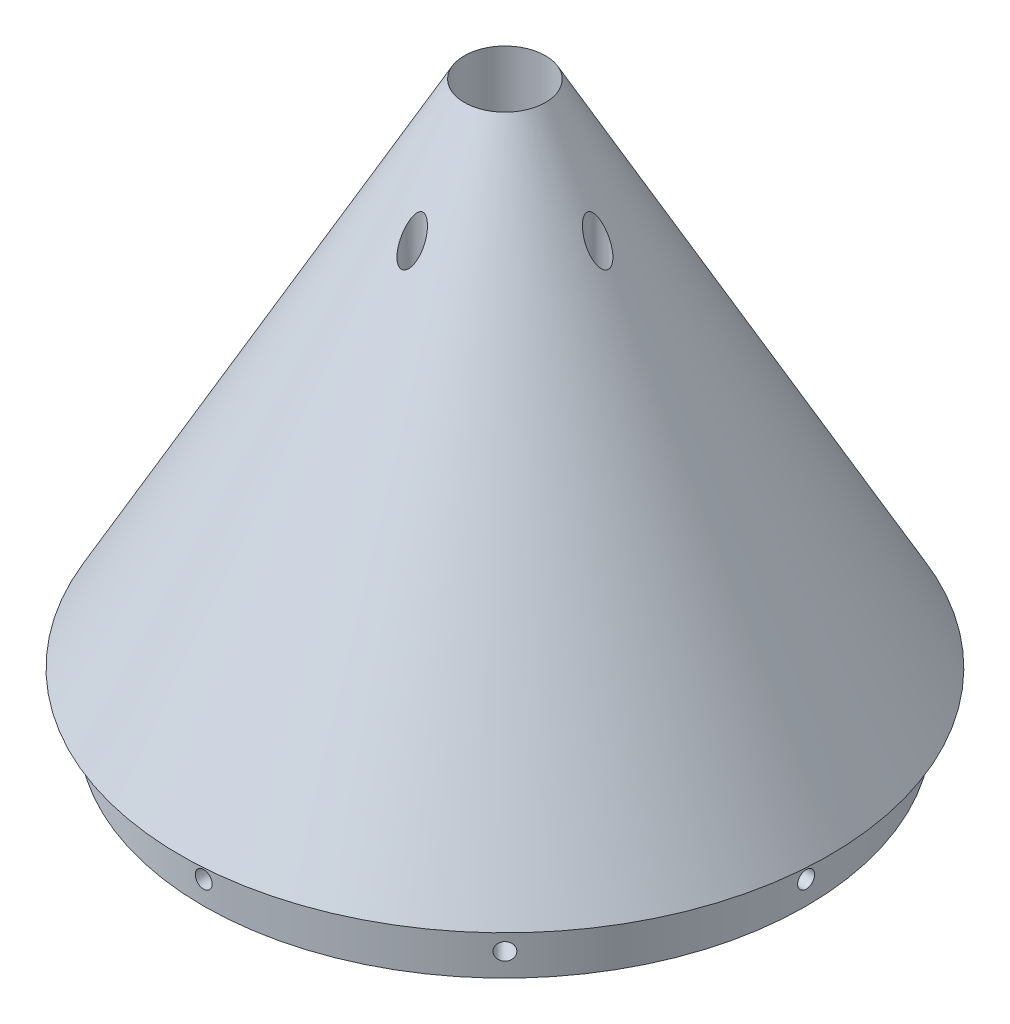
SolidWorks part; units mm, degrees
other "Markup1"
sketch "Sketch7" plane through (49.25, 60, 49.25) normal (0.0252, 0.7674, 0.6407) x (0.9994, -0.0343, 0.0017)
sketch "Sketch10" plane through (49.25, 120, 49.25) normal (0.0252, 0.7674, 0.6407) x (0.9994, -0.0343, 0.0017)
ref_plane "Front Plane" through (0, 0, 0) normal (0, 0, 1) x (1, 0, 0)
ref_plane "Top Plane" through (0, 0, 0) normal (0, 1, 0) x (1, 0, 0)
ref_plane "Right Plane" through (0, 0, 0) normal (1, 0, 0) x (0, 0, -1)
sketch "Sketch1" plane through (0, 0, 0) normal (0, 1, 0) x (1, 0, 0)
  circle A0 centre (0, 0) radius 65
  circle A1 centre (0, 0) radius 8.75
  dimension "D1" = 130
  dimension "D2" = 17.5
extrude "Boss-Extrude1" add sketch "Sketch1" along normal blind 12 contours A0
ref_plane "Plane1" through (-65, 0, 0) normal (-1, 0, 0) x (0, 0, 1)
sketch "Sketch2" plane through (-65, 0, 0) normal (-1, 0, 0) x (0, 0, 1)
  line L0 (0, 0) -> (0, 5)
  circle A0 centre (0, 5) radius 1.825
  dimension "D1" = 3.65
extrude "Cut-Extrude1" cut sketch "Sketch2" against normal blind 11
pattern_circular "CirPattern1" count 8 over 360 about axis through (0, 0, 0) along (0, 1, 0) of "Cut-Extrude1"
sketch "Sketch6" plane through (0, 0, 0) normal (0, 0, 1) x (1, 0, 0)
  line L3 (-8.75, 12) -> (-8.75, 122)
  line L7 (-8.75, 12) -> (-70, 12)
  line L8 (-70, 12) -> (-8.75, 122)
  dimension "D1" = 110
ref_axis "Axis1" through (0, -6, 0) along (0, 1, 0)
revolve "Revolve1" add sketch "Sketch6" angle 360 about axis through (0, -6, 0) along (0, 1, 0)
ref_plane "Plane2" through (0, 120, 0) normal (0, 1, 0) x (1, 0, 0)
sketch "Sketch9" plane through (0, 120, 0) normal (0, 1, 0) x (1, 0, 0)
  circle A0 centre (20, 0) radius 2.325
  dimension "D2" = 4.65
extrude "Cut-Extrude3" cut sketch "Sketch9" against normal blind 65
pattern_circular "CirPattern2" count 4 over 360 about axis through (0, 0, 0) along (0, 1, 0) of "Cut-Extrude3"
sketch "Sketch11" plane through (0, 0, 0) normal (0, -1, 0) x (1, 0, 0)
  circle A0 centre (0, 0) radius 17.5
extrude "Cut-Extrude5" cut sketch "Sketch11" against normal blind 53.25 contours A0
